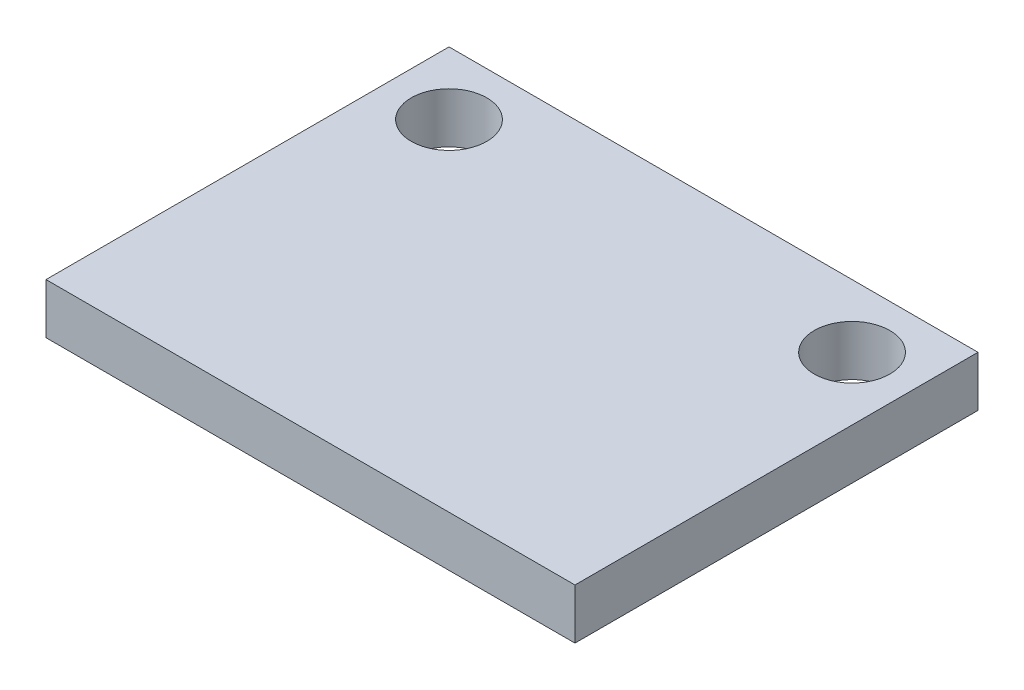
SolidWorks part; units mm, degrees
ref_plane "Front Plane" through (0, 0, 0) normal (0, 0, 1) x (1, 0, 0)
ref_plane "Top Plane" through (0, 0, 0) normal (0, 1, 0) x (1, 0, 0)
ref_plane "Right Plane" through (0, 0, 0) normal (1, 0, 0) x (0, 0, -1)
sketch "Sketch1" plane through (0, 0, 0) normal (0, 1, 0) x (1, 0, 0)
  line L1 (0, 0) -> (21, 0)
  line L2 (0, 0) -> (0, -16)
  line L3 (0, -16) -> (21, -16)
  line L4 (21, 0) -> (21, -16)
  circle A0 centre (2.5, -2.5) radius 1.5
  circle A1 centre (18.5, -2.5) radius 1.5
  dimension "D3" = 3
  dimension "D4" = 2.5
  dimension "D5" = 2.5
  dimension "D6" = 2.5
  dimension "D1" = 21
  dimension "D2" = 16
extrude "Boss-Extrude1" add sketch "Sketch1" along normal blind 2
